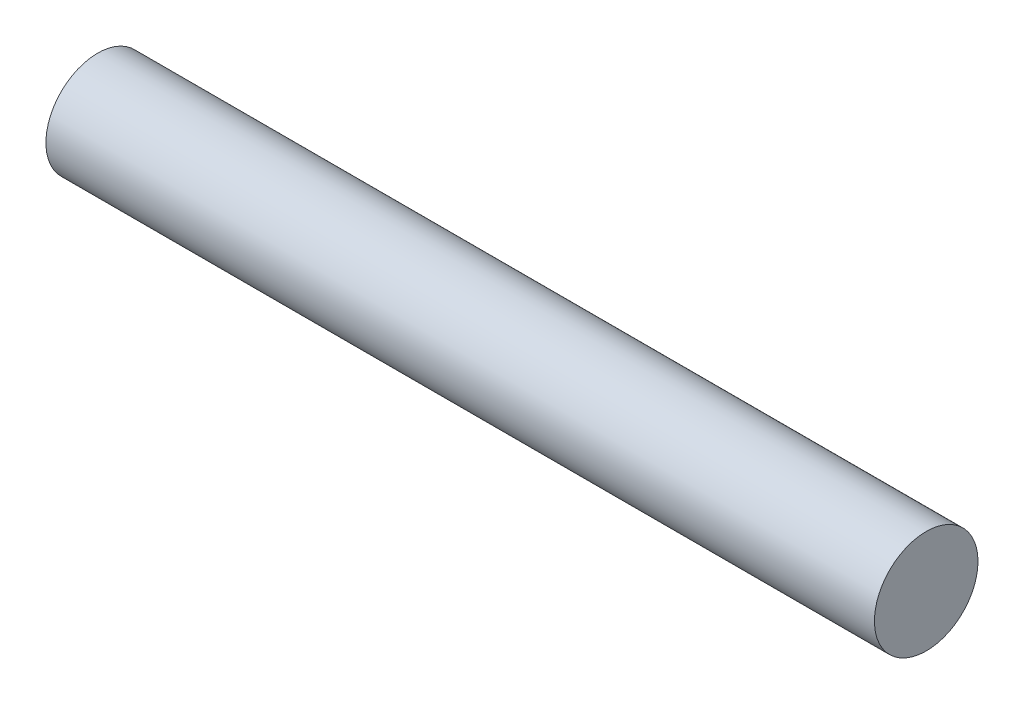
SolidWorks part; units mm, degrees
ref_plane "Front Plane" through (0, 0, 0) normal (0, 0, 1) x (1, 0, 0)
ref_plane "Top Plane" through (0, 0, 0) normal (0, 1, 0) x (1, 0, 0)
ref_plane "Right Plane" through (0, 0, 0) normal (1, 0, 0) x (0, 0, -1)
sketch "Sketch1" plane through (0, 0, 0) normal (1, 0, 0) x (0, 0, -1)
  circle A0 centre (0, 0) radius 0.375
  dimension "D1" = 0.75
extrude "Boss-Extrude1" add sketch "Sketch1" along normal blind 6
